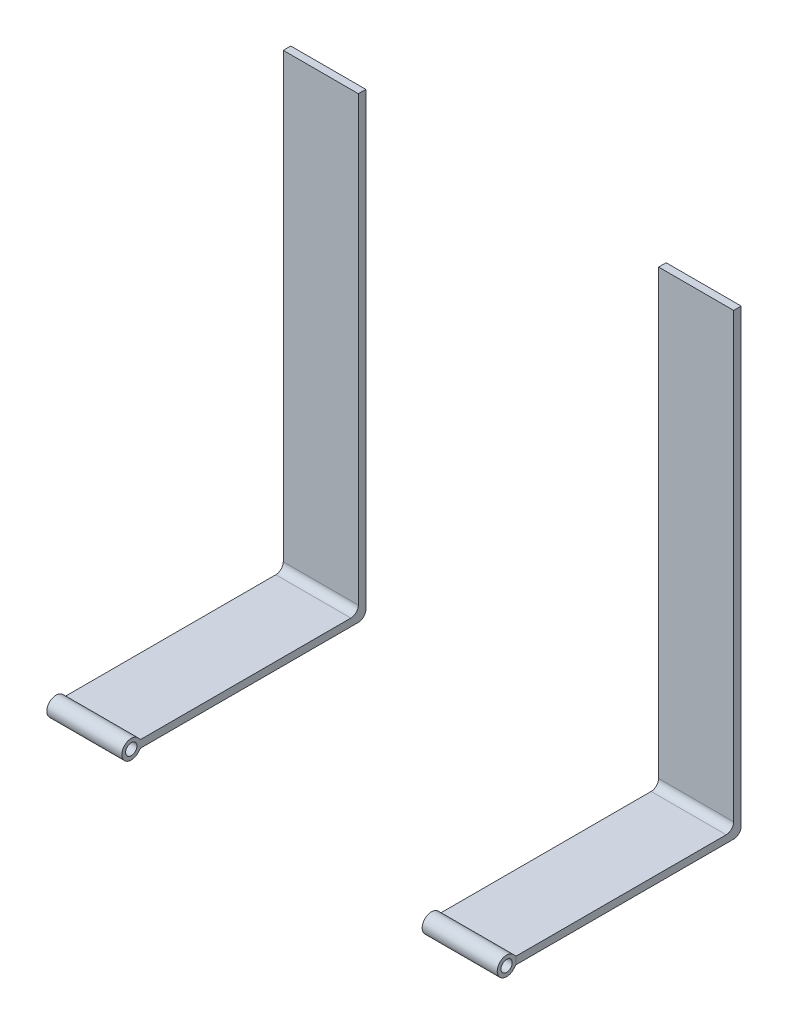
SolidWorks part; units mm, degrees
ref_plane "Front Plane" through (0, 0, 0) normal (0, 0, 1) x (1, 0, 0)
ref_plane "Top Plane" through (0, 0, 0) normal (0, 1, 0) x (1, 0, 0)
ref_plane "Right Plane" through (0, 0, 0) normal (1, 0, 0) x (0, 0, -1)
sketch "Sketch1" plane through (0, 0, 0) normal (0, 1, 0) x (1, 0, 0)
  line L1 (266.7, 101.6) -> (-266.7, 101.6)
  line L2 (266.7, 101.6) -> (266.7, -101.6)
  line L3 (266.7, -101.6) -> (-266.7, -101.6)
  line L4 (-266.7, 101.6) -> (-266.7, -101.6)
  line L5 (266.7, 101.6) -> (-266.7, -101.6) construction
  line L6 (266.7, -101.6) -> (-266.7, 101.6) construction
  line L7 (241.3, -76.2) -> (-241.3, -76.2)
  line L8 (241.3, -76.2) -> (241.3, 76.2)
  line L9 (241.3, 76.2) -> (-241.3, 76.2)
  line L10 (-241.3, -76.2) -> (-241.3, 76.2)
  line L11 (241.3, -76.2) -> (-241.3, 76.2) construction
  line L12 (241.3, 76.2) -> (-241.3, -76.2) construction
  point P0 (0, 0)
  point P6 (0, 0)
  dimension "D1" = 203.2
  dimension "D2" = 533.4
  dimension "D3" = 25.4
  dimension "D4" = 25.4
extrude "Boss-Extrude1" add sketch "Sketch1" along normal blind 2.54 contours L1 L4 L3 L2
fillet "Fillet1" radius 2.54 4 edges at (266.7, 1.27, -101.6) (266.7, 1.27, 101.6) (-266.7, 1.27, -101.6) (-266.7, 1.27, 101.6)
sketch "Sketch2" plane through (0, 0, -101.6) normal (0, 0, -1) x (-1, 0, 0)
  line L0 (0, 0) -> (0, 2.54) construction
  line L1 (-264.16, 2.54) -> (264.16, 2.54) construction
  line L2 (-264.16, 0) -> (264.16, 0) construction
  line L3 (50.8, 2.54) -> (76.2, 2.54)
  line L4 (50.8, 2.54) -> (50.8, 0)
  line L5 (50.8, 0) -> (76.2, 0)
  line L6 (76.2, 2.54) -> (76.2, 0)
  line L7 (-76.2, 2.54) -> (-76.2, 0)
  line L8 (-50.8, 0) -> (-76.2, 0)
  line L9 (-50.8, 2.54) -> (-50.8, 0)
  line L10 (-50.8, 2.54) -> (-76.2, 2.54)
  dimension "D1" = 50.8
  dimension "D2" = 25.4
extrude "Boss-Extrude2" add sketch "Sketch2" along normal blind 76.2
sketch "Sketch3" plane through (0, 2.54, 0) normal (0, 1, 0) x (1, 0, 0)
  line L0 (0, 0) -> (0, 158.1399) construction
  line L1 (-50.8, 177.8) -> (-50.8, 101.6) construction
  line L2 (-76.2, 177.8) -> (-50.8, 177.8)
  line L3 (-76.2, 177.8) -> (-76.2, 175.26)
  line L4 (-76.2, 175.26) -> (-50.8, 175.26)
  line L5 (-50.8, 177.8) -> (-50.8, 175.26)
  line L6 (50.8, 177.8) -> (50.8, 175.26)
  line L7 (76.2, 175.26) -> (50.8, 175.26)
  line L8 (76.2, 177.8) -> (76.2, 175.26)
  line L9 (76.2, 177.8) -> (50.8, 177.8)
  dimension "D1" = 2.54
extrude "Boss-Extrude3" add sketch "Sketch3" along normal blind 152.4
fillet "Fillet2" radius 2.54 2 edges at (63.5, 2.54, -175.26) (-63.5, 2.54, -175.26)
fillet "Fillet3" radius 2.54 2 edges at (-63.5, 0, -177.8) (63.5, 0, -177.8)
sketch "Sketch4" plane through (0, 2.54, 0) normal (0, 1, 0) x (1, 0, 0)
  line L0 (-264.16, -101.6) -> (264.16, -101.6) construction
  line L1 (266.7, -99.06) -> (266.7, 99.06) construction
  line L2 (264.16, 101.6) -> (76.2, 101.6) construction
  line L3 (50.8, 101.6) -> (-50.8, 101.6) construction
  line L4 (-266.7, 99.06) -> (-266.7, -99.06) construction
  line L5 (-76.2, 101.6) -> (-264.16, 101.6) construction
  line L6 (-264.16, -101.6) -> (264.16, -101.6)
  line L7 (266.7, -99.06) -> (266.7, 99.06)
  line L8 (264.16, 101.6) -> (76.2, 101.6)
  line L9 (50.8, 101.6) -> (-50.8, 101.6)
  line L10 (-266.7, 99.06) -> (-266.7, -99.06)
  line L11 (-76.2, 101.6) -> (-264.16, 101.6)
  line L12 (-76.2, 101.6) -> (-50.8, 101.6)
  line L13 (50.8, 101.6) -> (76.2, 101.6)
  arc A0 (-266.7, -99.06) -> (-264.16, -101.6) centre (-264.16, -99.06) ccw construction
  arc A1 (264.16, -101.6) -> (266.7, -99.06) centre (264.16, -99.06) ccw construction
  arc A2 (266.7, 99.06) -> (264.16, 101.6) centre (264.16, 99.06) ccw construction
  arc A3 (-264.16, 101.6) -> (-266.7, 99.06) centre (-264.16, 99.06) ccw construction
  arc A4 (-266.7, -99.06) -> (-264.16, -101.6) centre (-264.16, -99.06) ccw
  arc A5 (264.16, -101.6) -> (266.7, -99.06) centre (264.16, -99.06) ccw
  arc A6 (266.7, 99.06) -> (264.16, 101.6) centre (264.16, 99.06) ccw
  arc A7 (-264.16, 101.6) -> (-266.7, 99.06) centre (-264.16, 99.06) ccw
extrude "Cut-Extrude1" cut sketch "Sketch4" against normal through all
sketch "Sketch5" plane through (-76.2, 0, 0) normal (-1, 0, 0) x (0, 0, 1)
  line L0 (-101.6, 0) -> (-101.6, 2.54) construction
  line L1 (-175.26, 0) -> (-101.6, 0) construction
  line L2 (-172.72, 2.54) -> (-101.6, 2.54) construction
  line L3 (-175.26, 0) -> (-101.6, 0)
  line L4 (-172.72, 2.54) -> (-101.6, 2.54)
  line L5 (-101.6, 2.54) -> (-100.7241, 3.4597)
  line L6 (-101.6, 0) -> (-100.7241, -0.9197)
  line L7 (-101.6, 2.54) -> (-101.6, 0)
  circle A0 centre (-98.425, 1.27) radius 3.175
  circle A1 centre (-98.425, 1.27) radius 1.905
  point P5 (-97.4967, 1.27)
  line M9 (-101.6, 0) -> (-101.6, 2.54)
  dimension "D1" = 6.35
  dimension "D3" = 3.81
  dimension "D2" = 1.27
extrude "Boss-Extrude4" add sketch "Sketch5" against normal up to surface (25.4 mm away) contours A0 A1 | A0 L6 M9 | A0 L5 L7
mirror "Mirror4" about plane through (0, 0, 0) normal (1, 0, 0) of "Boss-Extrude4"
sketch "Sketch6" plane through (0, 2.54, 0) normal (0, 1, 0) x (1, 0, 0)
  line L0 (-76.2, 95.25) -> (76.2, 95.25) construction
  line L1 (-50.8, 101.6) -> (50.8, 101.6)
  line L2 (-50.8, 101.6) -> (-50.8, 95.25)
  line L3 (-50.8, 95.25) -> (50.8, 95.25)
  line L4 (50.8, 101.6) -> (50.8, 95.25)
  point P5 (0, 0)
  point P6 (0, 0)
extrude "Cut-Extrude2" cut sketch "Sketch6" against normal mid plane 25.4
